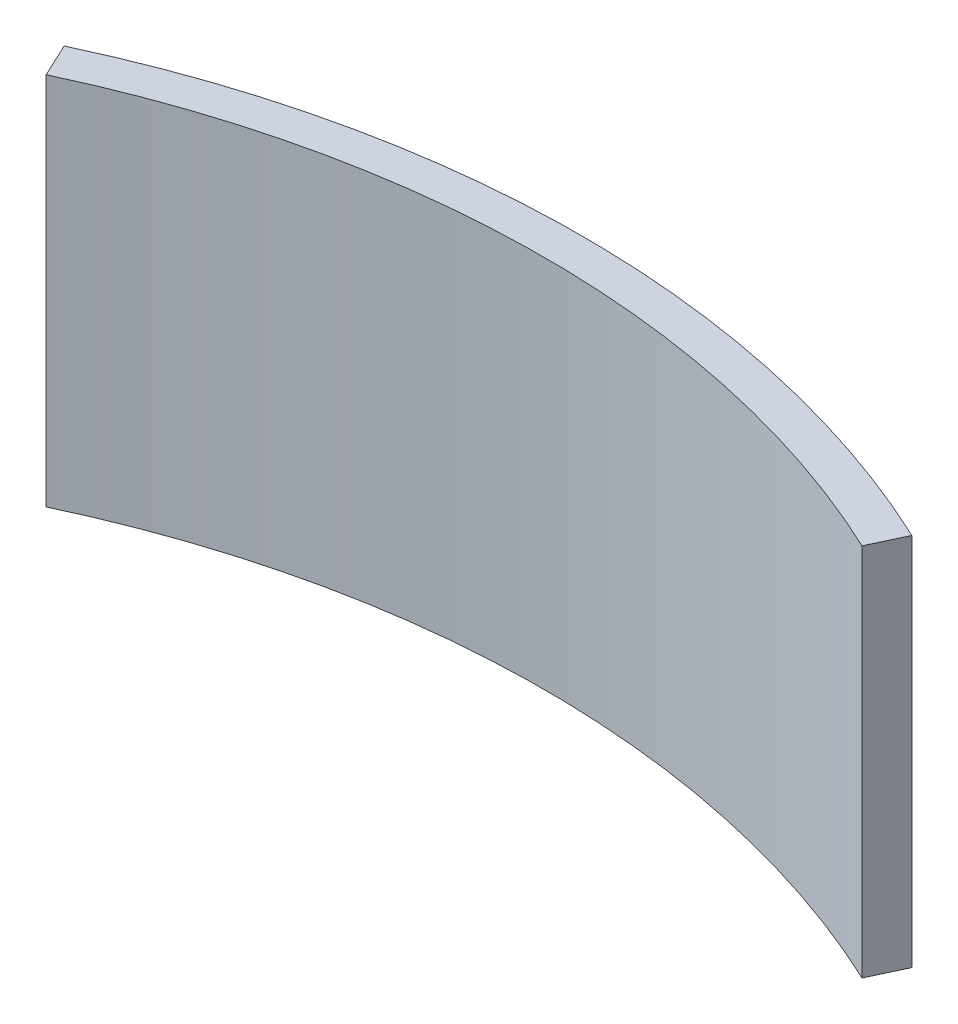
SolidWorks part; units mm, degrees
ref_plane "Front Plane" through (0, 0, 0) normal (0, 0, 1) x (1, 0, 0)
ref_plane "Top Plane" through (0, 0, 0) normal (0, 1, 0) x (1, 0, 0)
ref_plane "Right Plane" through (0, 0, 0) normal (1, 0, 0) x (0, 0, -1)
sketch "Sketch1" plane through (0, 0, 0) normal (0, 1, 0) x (1, 0, 0)
  line L0 (33.9742, 72.4276) -> (32.7002, 69.7115)
  line L1 (-33.9742, 72.4276) -> (-32.7002, 69.7115)
  arc A0 (33.9742, 72.4276) -> (-33.9742, 72.4276) centre (0, 0) ccw
  arc A1 (32.7002, 69.7115) -> (-32.7002, 69.7115) centre (0, 0) ccw
  point P4 (0, 80)
  point P8 (-33.9742, 72.4276)
  dimension "D1" = 80
  dimension "D2" = 3
extrude "Boss-Extrude1" add sketch "Sketch1" along normal blind 30
